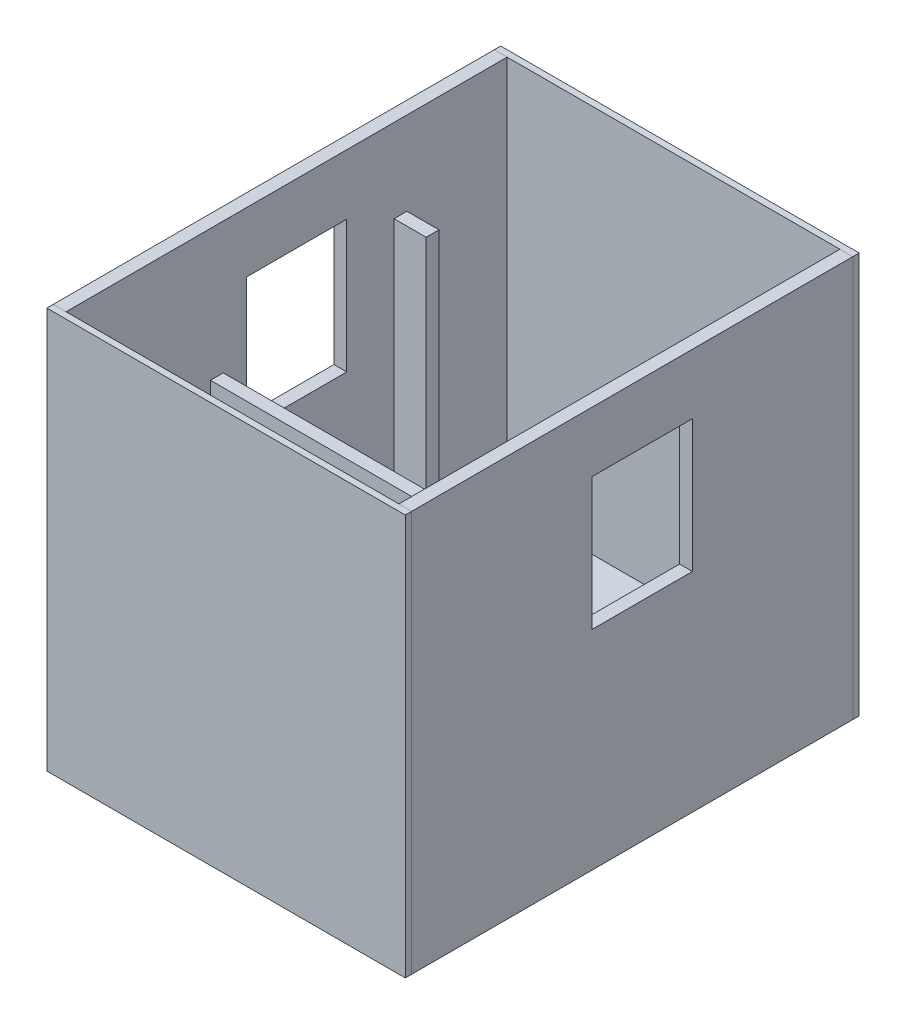
SolidWorks part; units mm, degrees
material "Pin"
ref_plane "Plan de face" through (0, 0, 0) normal (0, 0, 1) x (1, 0, 0)
ref_plane "Plan de dessus" through (0, 0, 0) normal (0, 1, 0) x (1, 0, 0)
ref_plane "Plan de droite" through (0, 0, 0) normal (1, 0, 0) x (0, 0, -1)
sketch "Esquisse1" plane through (0, 0, 0) normal (0, 1, 0) x (1, 0, 0)
  line L1 (0, 0) -> (415, 0)
  line L2 (0, 0) -> (0, 550)
  line L3 (0, 550) -> (415, 550)
  line L4 (415, 0) -> (415, 550)
  dimension "D1" = 550
  dimension "D2" = 415
extrude "Boss.-Extru.1" add sketch "Esquisse1" along normal blind 16
sketch "Esquisse2" plane through (0, 0, -500) normal (1, 0, 0) x (0, 0, -1)
  line L1 (-195, 16) -> (-182, 16)
  line L2 (-195, 16) -> (-195, 43)
  line L3 (-195, 43) -> (-182, 43)
  line L4 (-182, 16) -> (-182, 43)
  line L5 (50, 16) -> (50, 0) construction
  line L6 (-88, 16) -> (-75, 16)
  line L7 (-88, 16) -> (-88, 43)
  line L8 (-88, 43) -> (-75, 43)
  line L9 (-75, 16) -> (-75, 43)
  line L10 (50, 16) -> (-500, 16) construction
  dimension "D1" = 125
  dimension "D2" = 120
  dimension "D3" = 27
  dimension "D4" = 13
extrude "Boss.-Extru.2" add sketch "Esquisse2" along normal blind 335 from offset 40 separate body
sketch "Esquisse3" plane through (0, 0, 0) normal (0, 1, 0) x (1, 0, 0)
  line L0 (0, 0) -> (415, 0) construction
  line L1 (0, 550) -> (-16, 550)
  line L2 (0, 550) -> (0, 0)
  line L3 (0, 0) -> (-16, 0)
  line L4 (-16, 550) -> (-16, 0)
  line L6 (415, 550) -> (431, 550)
  line L7 (415, 550) -> (415, 0)
  line L8 (415, 0) -> (431, 0)
  line L9 (431, 550) -> (431, 0)
  dimension "D1" = 16
extrude "Boss.-Extru.3" add sketch "Esquisse3" along normal blind 500 separate body
sketch "Esquisse4" plane through (-16, 0, 0) normal (-1, 0, 0) x (0, 0, 1)
  line L0 (-550, 500) -> (-550, 0) construction
  line L1 (-350, 425) -> (-225, 425)
  line L2 (-350, 425) -> (-350, 260)
  line L3 (-350, 260) -> (-225, 260)
  line L4 (-225, 425) -> (-225, 260)
  line L5 (-550, 500) -> (0, 500) construction
  line L6 (0, 500) -> (0, 0) construction
  dimension "D1" = 125
  dimension "D2" = 165
  dimension "D3" = 75
  dimension "D4" = 200
  dimension "D5" = 225
extrude "Enlèv. mat.-Extru.1" cut sketch "Esquisse4" against normal through all
sketch "Esquisse5" plane through (0, 16, 0) normal (0, 1, 0) x (1, 0, 0)
  line L0 (0, 550) -> (0, 0) construction
  line L1 (415, 0) -> (415, 550) construction
  line L2 (375, 305) -> (40, 305) construction
  line L8 (0, 180) -> (415, 180)
  line L9 (0, 180) -> (0, 196)
  line L10 (0, 196) -> (415, 196)
  line L11 (415, 180) -> (415, 196)
  dimension "D1" = 16
  dimension "D2" = 109
extrude "Boss.-Extru.4" add sketch "Esquisse5" along normal blind 320 separate body
sketch "Esquisse6" plane through (0, 0, -550) normal (0, 0, -1) x (-1, 0, 0)
  line L1 (-431, 0) -> (16, 0)
  line L2 (-431, 0) -> (-431, 500)
  line L3 (-431, 500) -> (16, 500)
  line L4 (16, 0) -> (16, 500)
extrude "Boss.-Extru.5" add sketch "Esquisse6" along normal blind 8 separate body
sketch "Esquisse7" plane through (0, 0, 0) normal (0, 0, 1) x (1, 0, 0)
  line L1 (-16, 500) -> (431, 500)
  line L2 (-16, 500) -> (-16, 0)
  line L3 (-16, 0) -> (431, 0)
  line L4 (431, 500) -> (431, 0)
extrude "Boss.-Extru.6" add sketch "Esquisse7" along normal blind 8 separate body
sketch "Esquisse8" plane through (0, 500, 0) normal (0, 1, 0) x (1, 0, 0)
  line L1 (-16, 558) -> (431, 558)
  line L2 (-16, 558) -> (-16, -8)
  line L3 (-16, -8) -> (431, -8)
  line L4 (431, 558) -> (431, -8)
extrude "Boss.-Extru.7" [suppressed] add sketch "Esquisse8" along normal blind 8 separate body
sketch "Esquisse9" plane through (0, 16, 0) normal (0, 1, 0) x (1, 0, 0)
  line L0 (0, 0) -> (0, 550) construction
  line L1 (0, 409) -> (40, 409)
  line L2 (0, 409) -> (0, 425)
  line L3 (0, 425) -> (40, 425)
  line L4 (40, 409) -> (40, 425)
  line L8 (415, 0) -> (415, 550) construction
  line L9 (415, 425) -> (375, 425)
  line L10 (415, 425) -> (415, 409)
  line L11 (415, 409) -> (375, 409)
  line L12 (375, 425) -> (375, 409)
  line L13 (375, 425) -> (40, 425) construction
  dimension "D1" = 40
  dimension "D2" = 16
extrude "Boss.-Extru.8" add sketch "Esquisse9" along normal blind 380 separate body
sketch "Esquisse10" plane through (0, 16, 0) normal (0, 1, 0) x (1, 0, 0)
  line L0 (0, 180) -> (415, 180) construction
  line L1 (285, 180) -> (301, 180)
  line L2 (285, 180) -> (285, 0)
  line L3 (285, 0) -> (301, 0)
  line L4 (301, 180) -> (301, 0)
  line L5 (431, 0) -> (-16, 0) construction
  line L6 (0, 0) -> (0, 550) construction
  dimension "D1" = 16
  dimension "D2" = 285
extrude "Boss.-Extru.9" add sketch "Esquisse10" along normal blind 180 separate body
